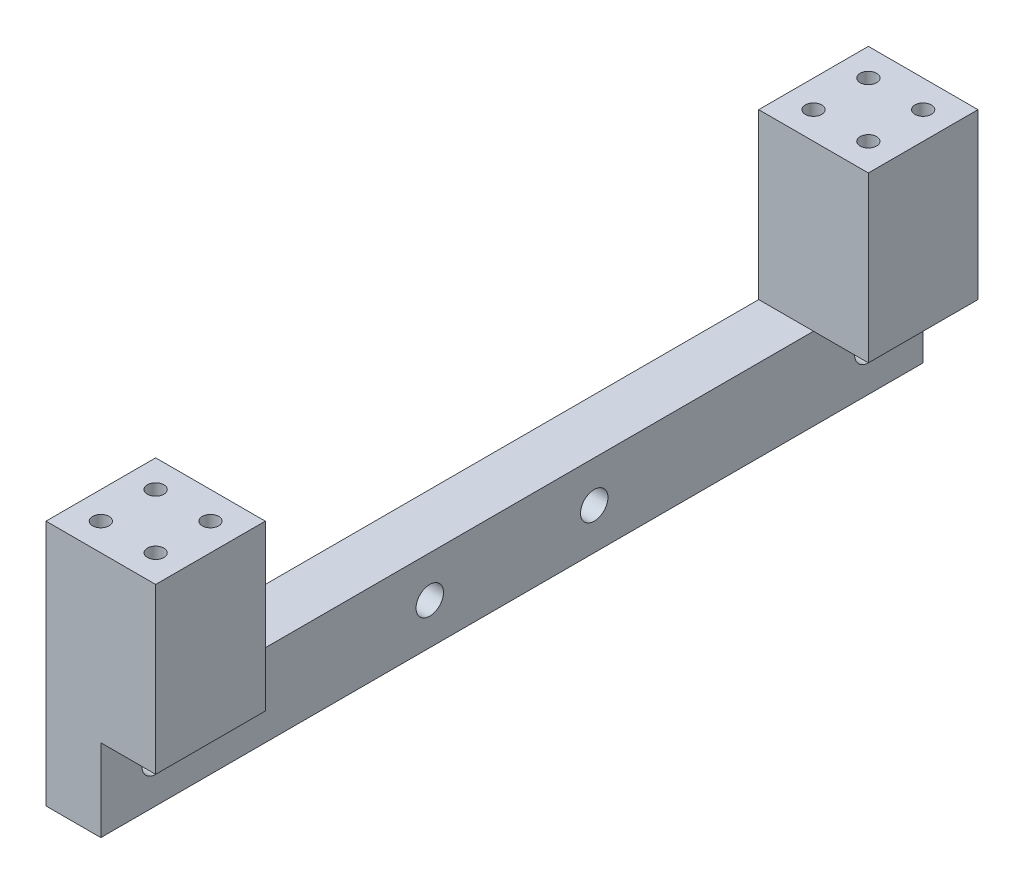
SolidWorks part; units mm, degrees
ref_plane "前视基准面" through (0, 0, 0) normal (0, 0, 1) x (1, 0, 0)
ref_plane "上视基准面" through (0, 0, 0) normal (0, 1, 0) x (1, 0, 0)
ref_plane "右视基准面" through (0, 0, 0) normal (1, 0, 0) x (0, 0, -1)
sketch "草图1" plane through (0, 0, 0) normal (0, 1, 0) x (1, 0, 0)
  line L1 (-5, -75) -> (5, -75)
  line L2 (-5, -75) -> (-5, 75)
  line L3 (-5, 75) -> (5, 75)
  line L4 (5, -75) -> (5, 75)
  line L5 (-5, -75) -> (5, 75) construction
  line L6 (-5, 75) -> (5, -75) construction
  point P0 (0, 0)
  dimension "D1" = 10
  dimension "D2" = 150
extrude "凸台-拉伸1" add sketch "草图1" along normal blind 15
sketch "草图2" plane through (0, 15, 0) normal (0, 1, 0) x (1, 0, 0)
  line L0 (5, -75) -> (5, 75) construction
  line L1 (15, 55) -> (-5, 55)
  line L2 (15, 55) -> (15, 75)
  line L3 (15, 75) -> (-5, 75)
  line L4 (-5, 55) -> (-5, 75)
  line L5 (15, 55) -> (-5, 75) construction
  line L6 (15, 75) -> (-5, 55) construction
  line L8 (15, -55) -> (-5, -55)
  line L9 (15, -55) -> (15, -75)
  line L10 (15, -75) -> (-5, -75)
  line L11 (-5, -55) -> (-5, -75)
  line L12 (15, -55) -> (-5, -75) construction
  line L13 (15, -75) -> (-5, -55) construction
  point P0 (5, 65)
  point P8 (5, -65)
  dimension "D1" = 20
  dimension "D2" = 20
extrude "凸台-拉伸2" add sketch "草图2" along normal blind 30
sketch "草图3" plane through (-5, 0, 0) normal (-1, 0, 0) x (0, 0, 1)
  line L2 (75, 45) -> (75, 0) construction
  line L3 (-55, 15) -> (55, 15) construction
  circle A0 centre (-65, 7.5) radius 2.5
  circle A1 centre (-15, 7.5) radius 2.5
  circle A2 centre (15, 7.5) radius 2.5
  circle A3 centre (65, 7.5) radius 2.5
  dimension "D5" = 5
  dimension "D6" = 5
  dimension "D7" = 5
  dimension "D8" = 5
  dimension "D1" = 10
  dimension "D2" = 50
  dimension "D3" = 30
  dimension "D4" = 50
  dimension "D9" = 7.5
extrude "切除-拉伸1" cut sketch "草图3" against normal through all
sketch "草图4" plane through (0, 45, 0) normal (0, 1, 0) x (1, 0, 0)
  line L0 (15, 75) -> (-5, 75) construction
  line L1 (-5, 75) -> (-5, 55) construction
  line L2 (-5, 55) -> (5, 55) construction
  line L3 (15, 55) -> (15, 75) construction
  line L4 (-5, 55) -> (15, 55) construction
  circle A0 centre (0, 70) radius 1.5
  circle A1 centre (10, 70) radius 1.5
  circle A2 centre (0, 60) radius 1.5
  circle A3 centre (10, 60) radius 1.5
  dimension "D1" = 3
  dimension "D2" = 3
  dimension "D3" = 3
  dimension "D4" = 3
  dimension "D5" = 5
  dimension "D6" = 5
  dimension "D7" = 5
  dimension "D8" = 5
  dimension "D9" = 5
  dimension "D10" = 5
  dimension "D11" = 5
  dimension "D12" = 5
extrude "切除-拉伸2" cut sketch "草图4" against normal blind 10
mirror "镜向1" about plane through (0, 0, 0) normal (0, 0, 1) of "切除-拉伸2"
